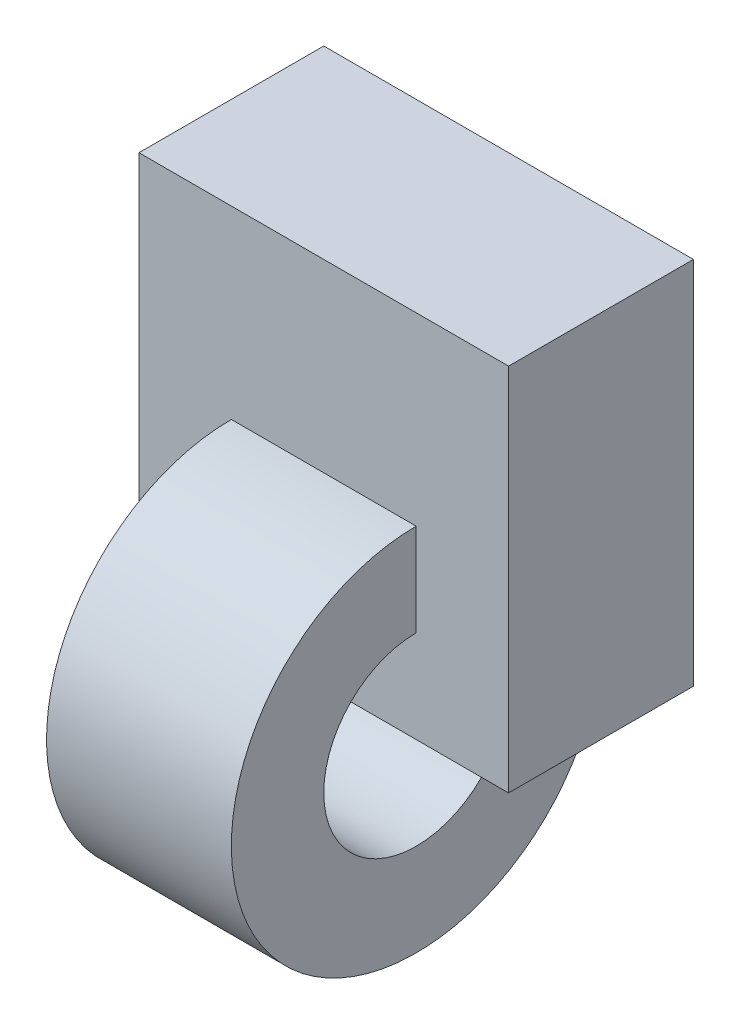
SolidWorks part; units mm, degrees
ref_plane "前视基准面" through (0, 0, 0) normal (0, 0, 1) x (1, 0, 0)
ref_plane "上视基准面" through (0, 0, 0) normal (0, 1, 0) x (1, 0, 0)
ref_plane "右视基准面" through (0, 0, 0) normal (1, 0, 0) x (0, 0, -1)
other "Configuration Table"
sketch "草图1" plane through (0, 0, 0) normal (0, 0, 1) x (1, 0, 0)
  line L1 (0, 0) -> (20, 0)
  line L2 (0, 0) -> (0, 20)
  line L3 (0, 20) -> (20, 20)
  line L4 (20, 0) -> (20, 20)
extrude "BaseBox" add sketch "草图1" along normal blind 10
sketch "草图2" plane through (0, 0, 10) normal (0, 0, 1) x (1, 0, 0)
  line L1 (5, 5) -> (15, 5)
  line L2 (5, 5) -> (5, 10)
  line L3 (5, 10) -> (15, 10)
  line L4 (15, 5) -> (15, 10)
revolve "RevolveAxisEdge" add sketch "草图2" angle 360 about axis through (0, 0, 10) along (1, 0, 0)
